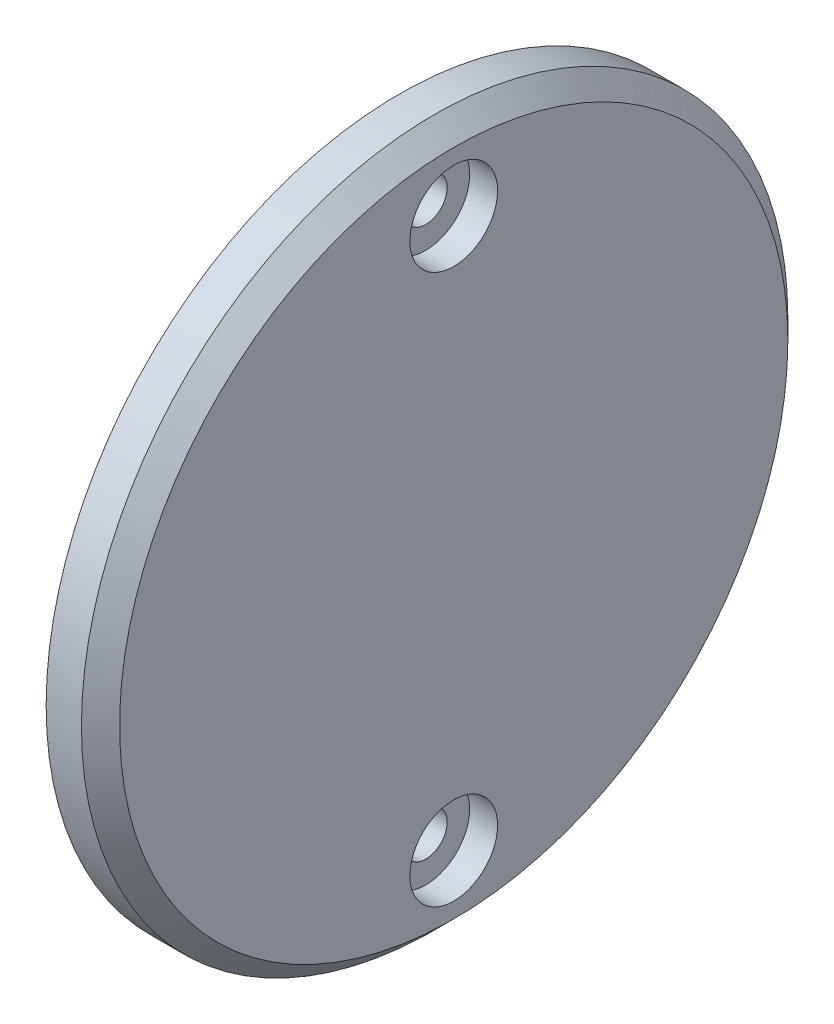
SolidWorks part; units mm, degrees
ref_plane "Front Plane" through (0, 0, 0) normal (0, 0, 1) x (1, 0, 0)
ref_plane "Top Plane" through (0, 0, 0) normal (0, 1, 0) x (1, 0, 0)
ref_plane "Right Plane" through (0, 0, 0) normal (1, 0, 0) x (0, 0, -1)
sketch "Sketch1" plane through (0, 0, 0) normal (1, 0, 0) x (0, 0, -1)
  circle A0 centre (0, 0) radius 55.5625
  dimension "D1" = 111.125
extrude "Boss-Extrude1" add sketch "Sketch1" along normal blind 8.55
chamfer "Chamfer1" distance 3 angle 45 1 edges at (8.55, 0, -55.5625)
sketch "Sketch3" plane through (8.55, 0, 0) normal (1, 0, 0) x (0, 0, -1)
  line L0 (0, -43.225) -> (0, 43.225)
  circle A0 centre (0, 43.225) radius 6.9
  circle A1 centre (0, -43.225) radius 6.9
  point P9 (0, 0)
  dimension "D1" = 13.8
  dimension "D2" = 13.8
  dimension "D3" = 86.45
extrude "Cut-Extrude1" cut sketch "Sketch3" against normal blind 4.4
sketch "Sketch4" plane through (4.15, 0, 0) normal (1, 0, 0) x (0, 0, -1)
  circle A0 centre (0, 43.225) radius 3.375
  circle A1 centre (0, -43.225) radius 3.375
  dimension "D1" = 6.75
  dimension "D2" = 6.75
extrude "Cut-Extrude2" cut sketch "Sketch4" against normal up to surface (4.15 mm away) up to face at (0, 0, -55.5625)
sketch "AssemblyConstruction" plane through (0, 0, 0) normal (-1, 0, 0) x (0, 0, 1)
  line L0 (0, 43.225) -> (0, -43.225) construction
